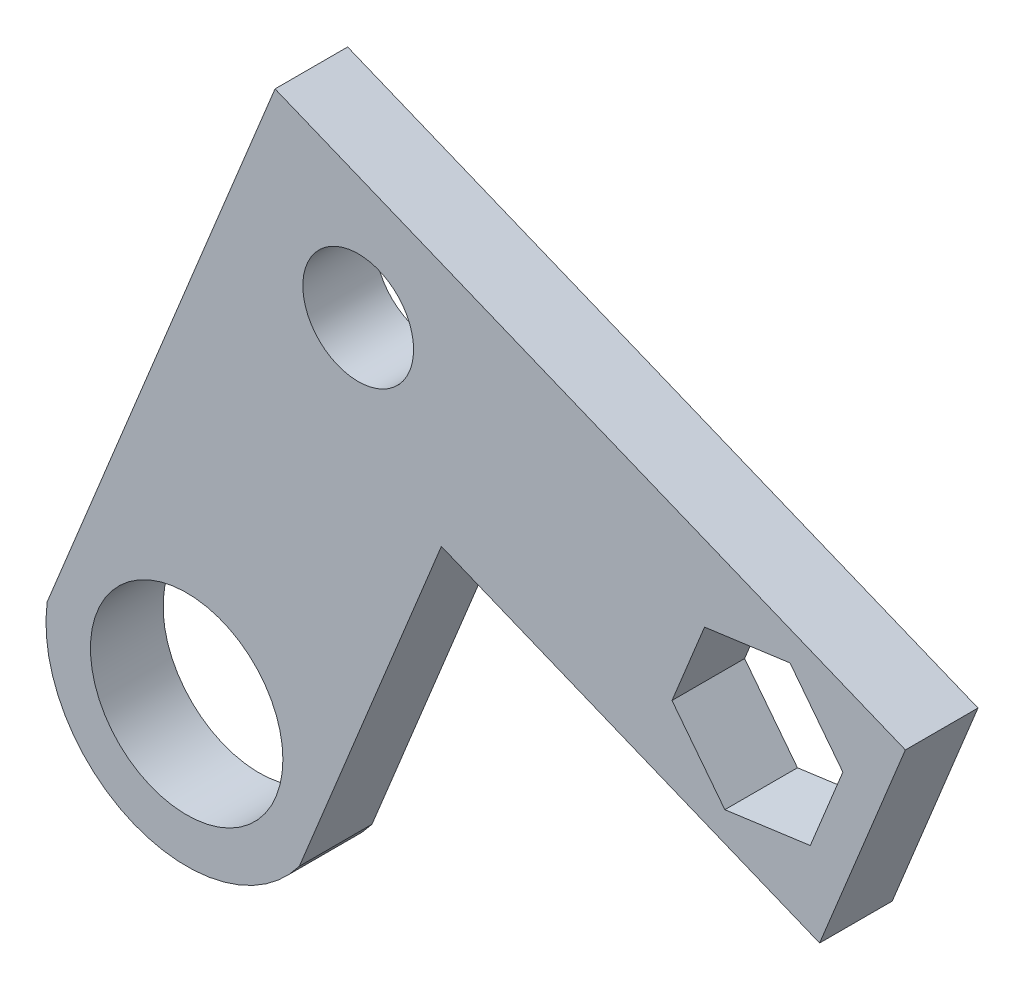
SolidWorks part; units mm, degrees
ref_plane "前基準面" through (0, 0, 0) normal (0, 0, 1) x (1, 0, 0)
ref_plane "上基準面" through (0, 0, 0) normal (0, 1, 0) x (1, 0, 0)
ref_plane "右基準面" through (0, 0, 0) normal (1, 0, 0) x (0, 0, -1)
sketch "草圖1" plane through (0, 0, 0) normal (0, 0, 1) x (1, 0, 0)
  line L0 (-42.6847, 14.987) -> (26.7532, -13.357)
  line L5 (26.7532, -13.357) -> (17.3052, -36.503)
  line L6 (17.3052, -36.503) -> (-24.3576, -19.4966)
  line L7 (-24.3576, -19.4966) -> (-40.0054, -57.831)
  line L9 (-67.7805, -46.4934) -> (-42.6847, 14.987)
  line L10 (22.0292, -24.93) -> (-47.4087, 3.414) construction
  line L11 (-57.1411, -60.1197) -> (-28.7971, 9.3182) construction
  line L12 (19.8684, -18.9175) -> (1.044, -21.4945) construction
  line L13 (16.2782, -27.713) -> (4.6342, -12.699) construction
  line L14 (6.866, -29.0015) -> (14.0464, -11.4105) construction
  line L15 (1.044, -21.4945) -> (4.6342, -12.699)
  line L16 (4.6342, -12.699) -> (14.0464, -11.4105)
  line L17 (14.0464, -11.4105) -> (19.8684, -18.9175)
  line L18 (19.8684, -18.9175) -> (16.2782, -27.713)
  line L19 (16.2782, -27.713) -> (6.866, -29.0015)
  line L20 (6.866, -29.0015) -> (1.044, -21.4945)
  circle A0 centre (10.4562, -20.206) radius 5.1 construction
  circle A1 centre (-33.5211, -2.2548) radius 6.1
  circle A2 centre (-52.4171, -48.5467) radius 10.6
  circle A3 centre (-52.4171, -48.5467) radius 15.5 construction
  arc A4 (-67.7805, -46.4934) -> (-40.0054, -57.831) centre (-52.4171, -48.5467) ccw
  point P12 (-33.5211, -2.2548)
  point P21 (10.4562, -20.206)
  point P23 (10.4562, -20.206)
  point P30 (10.4562, -20.206)
  point P34 (10.4562, -20.206)
  dimension "D5" = 10.2
  dimension "D8" = 12.2
  dimension "D9" = 21.2
  dimension "D11" = 60
  dimension "D1" = 25
  dimension "D4" = 75
  dimension "D6" = 12.5
  dimension "D7" = 12.5
  dimension "D12" = 60
extrude "填料-伸長1" add sketch "草圖1" against normal blind 8
